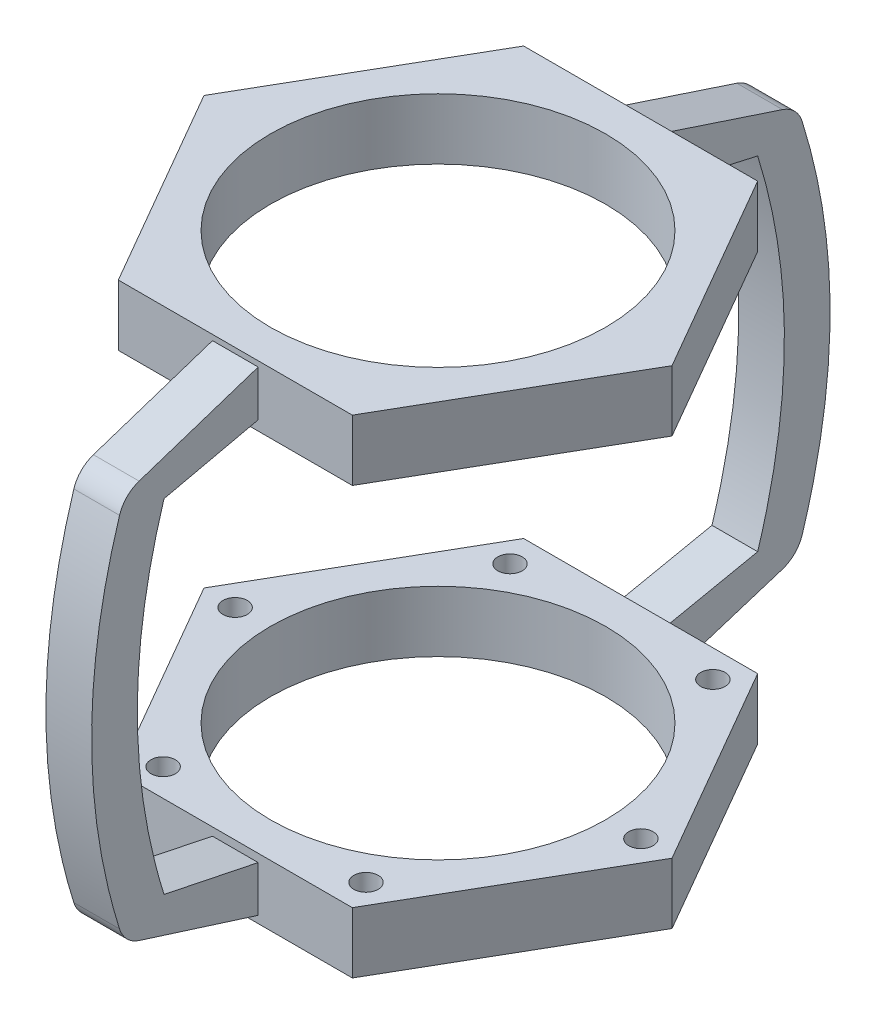
SolidWorks part; units mm, degrees
ref_plane "前视基准面" through (0, 0, 0) normal (0, 0, 1) x (1, 0, 0)
ref_plane "上视基准面" through (0, 0, 0) normal (0, 1, 0) x (1, 0, 0)
ref_plane "右视基准面" through (0, 0, 0) normal (1, 0, 0) x (0, 0, -1)
other "Configuration Table"
sketch "草图1" plane through (0, 0, 0) normal (0, 1, 0) x (1, 0, 0)
  line L1 (76.8103, 0) -> (38.4051, 66.5197)
  line L2 (38.4051, 66.5197) -> (-38.4051, 66.5197)
  line L3 (-38.4051, 66.5197) -> (-76.8103, 0)
  line L4 (-76.8103, 0) -> (-38.4051, -66.5197)
  line L5 (-38.4051, -66.5197) -> (38.4051, -66.5197)
  line L6 (38.4051, -66.5197) -> (76.8103, 0)
  circle A0 centre (0, 0) radius 55.01
  circle A1 centre (0, 0) radius 66.5197 construction
  dimension "D1" = 110.02
extrude "凸台-拉伸1" add sketch "草图1" along normal blind 20
ref_plane "基准面1" through (0, 80, 0) normal (0, 1, 0) x (1, 0, 0)
mirror "镜向5" about plane through (0, 80, 0) normal (0, 1, 0) of bodies 106
sketch "草图4" plane through (0, 0, 66.5197) normal (0, 0, 1) x (1, 0, 0)
  line L1 (-7.5291, 156.6879) -> (7.4709, 156.6879)
  line L2 (-7.5291, 156.6879) -> (-7.5291, 141.6879)
  line L3 (-7.5291, 141.6879) -> (7.4709, 141.6879)
  line L4 (7.4709, 156.6879) -> (7.4709, 141.6879)
  line L5 (-7.5291, 156.6879) -> (7.4709, 141.6879) construction
  line L6 (-7.5291, 141.6879) -> (7.4709, 156.6879) construction
  line L7 (-6.4385, 16.8678) -> (8.5615, 16.8678)
  line L8 (-6.4385, 16.8678) -> (-6.4385, 1.8678)
  line L9 (-6.4385, 1.8678) -> (8.5615, 1.8678)
  line L10 (8.5615, 16.8678) -> (8.5615, 1.8678)
  line L11 (-6.4385, 16.8678) -> (8.5615, 1.8678) construction
  line L12 (-6.4385, 1.8678) -> (8.5615, 16.8678) construction
  point P0 (-0.0291, 149.1879)
  point P5 (1.0615, 9.3678)
  dimension "D1" = 15
  dimension "D2" = 15
  dimension "D3" = 15
  dimension "D4" = 15
sketch "草图5" plane through (0, 0, 0) normal (1, 0, 0) x (0, 0, -1)
  line L0 (0, 0) -> (0, 167.1453) construction
sketch "草图6" plane through (0, 80, 0) normal (0, 1, 0) x (1, 0, 0)
  line L0 (0, 0) -> (0, 71.5983) construction
  line L1 (0, 71.5983) -> (0, -78.7582) construction
  line L3 (5.4508, -102.5) -> (20.4508, -102.5)
  line L4 (5.4508, -102.5) -> (5.4508, -117.5)
  line L5 (5.4508, -117.5) -> (20.4508, -117.5)
  line L6 (20.4508, -102.5) -> (20.4508, -117.5)
  line L7 (5.4508, -102.5) -> (20.4508, -117.5) construction
  line L8 (5.4508, -117.5) -> (20.4508, -102.5) construction
  point P3 (12.9508, -110)
  dimension "D1" = 15
  dimension "D2" = 15
  dimension "D3" = 110
sketch "草图7" plane through (0, 0, 0) normal (1, 0, 0) x (0, 0, -1)
  line L0 (0, 80) -> (-141.9577, 161.9593) construction
  line L1 (0, 0) -> (0, 167.1453) construction
  line L2 (71.5983, 80) -> (-78.7582, 80) construction
  line L3 (0, 80) -> (-138.8126, -0.1435) construction
ref_plane "基准面2" through (0, 60, -34.641) normal (0, 0.866, -0.5) x (0, 0.5, 0.866)
ref_plane "基准面3" through (0, 60, 34.641) normal (0, 0.866, 0.5) x (0, -0.5, 0.866)
sketch "草图9" plane through (0, 60, -34.641) normal (0, 0.866, -0.5) x (0, 0.5, 0.866)
  line L0 (40, 0) -> (203.9186, 0) construction
  line L2 (152.5, 7.5) -> (167.5, 7.5)
  line L3 (152.5, 7.5) -> (152.5, -7.5)
  line L4 (152.5, -7.5) -> (167.5, -7.5)
  line L5 (167.5, 7.5) -> (167.5, -7.5)
  line L6 (152.5, 7.5) -> (167.5, -7.5) construction
  line L7 (152.5, -7.5) -> (167.5, 7.5) construction
  point P2 (160, 0)
  dimension "D1" = 15
  dimension "D2" = 15
  dimension "D3" = 120
sketch "草图10" plane through (0, 60, 34.641) normal (0, 0.866, 0.5) x (0, -0.5, 0.866)
  line L0 (-40, 0) -> (120.287, 0) construction
  line L1 (72.5, 7.5) -> (87.5, 7.5)
  line L2 (72.5, 7.5) -> (72.5, -7.5)
  line L3 (72.5, -7.5) -> (87.5, -7.5)
  line L4 (87.5, 7.5) -> (87.5, -7.5)
  line L5 (72.5, 7.5) -> (87.5, -7.5) construction
  line L6 (72.5, -7.5) -> (87.5, 7.5) construction
  point P0 (80, 0)
  dimension "D1" = 15
  dimension "D2" = 15
  dimension "D3" = 120
sketch "草图11" plane through (0, 80, 0) normal (0, 1, 0) x (1, 0, 0)
  line L0 (0, 0) -> (0, -138.8126) construction
  line L1 (-7.5, -106.1923) -> (7.5, -106.1923)
  line L2 (-7.5, -106.1923) -> (-7.5, -121.1923)
  line L3 (-7.5, -121.1923) -> (7.5, -121.1923)
  line L4 (7.5, -106.1923) -> (7.5, -121.1923)
  line L5 (-7.5, -106.1923) -> (7.5, -121.1923) construction
  line L6 (-7.5, -121.1923) -> (7.5, -106.1923) construction
  point P0 (0, -113.6923)
  dimension "D1" = 15
  dimension "D2" = 15
loft "放样1" add profiles "草图9", "草图11", "草图10"
ref_plane "基准面7" through (0, 0, 66.52) normal (0, 0, 1) x (1, 0, 0)
sketch "草图16" plane through (0, 0, 66.52) normal (0, 0, 1) x (1, 0, 0)
  line L0 (0, 0) -> (0, 167.1453) construction
  line L1 (-7.5, 158.2204) -> (7.5, 158.2204)
  line L2 (-7.5, 158.2204) -> (-7.5, 143.2204)
  line L3 (-7.5, 143.2204) -> (7.5, 143.2204)
  line L4 (7.5, 158.2204) -> (7.5, 143.2204)
  line L5 (-7.5, 158.2204) -> (7.5, 143.2204) construction
  line L6 (-7.5, 143.2204) -> (7.5, 158.2204) construction
  line L8 (-7.5, 17.4834) -> (7.5, 17.4834)
  line L9 (-7.5, 17.4834) -> (-7.5, 2.4834)
  line L10 (-7.5, 2.4834) -> (7.5, 2.4834)
  line L11 (7.5, 17.4834) -> (7.5, 2.4834)
  line L12 (-7.5, 17.4834) -> (7.5, 2.4834) construction
  line L13 (-7.5, 2.4834) -> (7.5, 17.4834) construction
  point P0 (0, 150.7204)
  point P7 (0, 9.9834)
  dimension "D1" = 15
  dimension "D2" = 15
  dimension "D3" = 15
loft "放样3" add section "草图16" section face at (0, 140, 103.923)
sketch "草图18" plane through (0, 0, 66.52) normal (0, 0, 1) x (1, 0, 0)
  line L0 (0, 0) -> (0, 167.1453) construction
  line L1 (-7.5, 17.3623) -> (7.5, 17.3623)
  line L2 (-7.5, 17.3623) -> (-7.5, 2.3623)
  line L3 (-7.5, 2.3623) -> (7.5, 2.3623)
  line L4 (7.5, 17.3623) -> (7.5, 2.3623)
  line L5 (-7.5, 17.3623) -> (7.5, 2.3623) construction
  line L6 (-7.5, 2.3623) -> (7.5, 17.3623) construction
  point P0 (0, 9.8623)
  dimension "D1" = 15
  dimension "D2" = 15
loft "放样6" add profiles "草图18" section "草图18" section face at (0, 20, 103.923)
fillet "圆角2" radius 10 1 edges
fillet "圆角3" radius 10 1 edges
mirror "镜向6" about plane through (0, 0, 0) normal (0, 0, 1) of bodies 115
sketch "草图19" plane through (0, 0, 0) normal (0, -1, 0) x (1, 0, 0)
  line L0 (38.4051, 66.5197) -> (0, 0) construction
  line L1 (0, 0) -> (38.4051, -66.5197) construction
  line L2 (38.4051, -66.5197) -> (-38.4051, 66.5197) construction
  line L3 (-38.4051, 66.5197) -> (0, 0) construction
  line L4 (0, 0) -> (-38.4051, -66.5197) construction
  line L5 (-38.4051, -66.5197) -> (-76.8103, 0) construction
  line L6 (38.4051, -66.5197) -> (-38.4051, -66.5197) construction
  line L7 (27.505, 47.6401) -> (49.3053, 47.6401) construction
  line L8 (38.4051, 66.5197) -> (76.8103, 0) construction
  line L9 (49.3053, 47.6401) -> (38.4051, 66.5197) construction
  line L10 (38.4051, 66.5197) -> (17.6085, 66.5197) construction
  line L11 (-38.4051, 66.5197) -> (38.4051, 66.5197) construction
  line L12 (17.6085, 66.5197) -> (27.505, 47.6401) construction
  line L13 (17.6085, 66.5197) -> (49.3053, 47.6401) construction
  circle A1 centre (0, 0) radius 55.01 construction
  circle A2 centre (33.4569, 57.0799) radius 4
  dimension "D1" = 8
extrude "切除-拉伸2" cut sketch "草图19" against normal blind 20 contours A2
pattern_circular "阵列(圆周)2" count 6 over 360 about axis through (0, 0, 0) along (0, 1, 0) of "切除-拉伸2"
